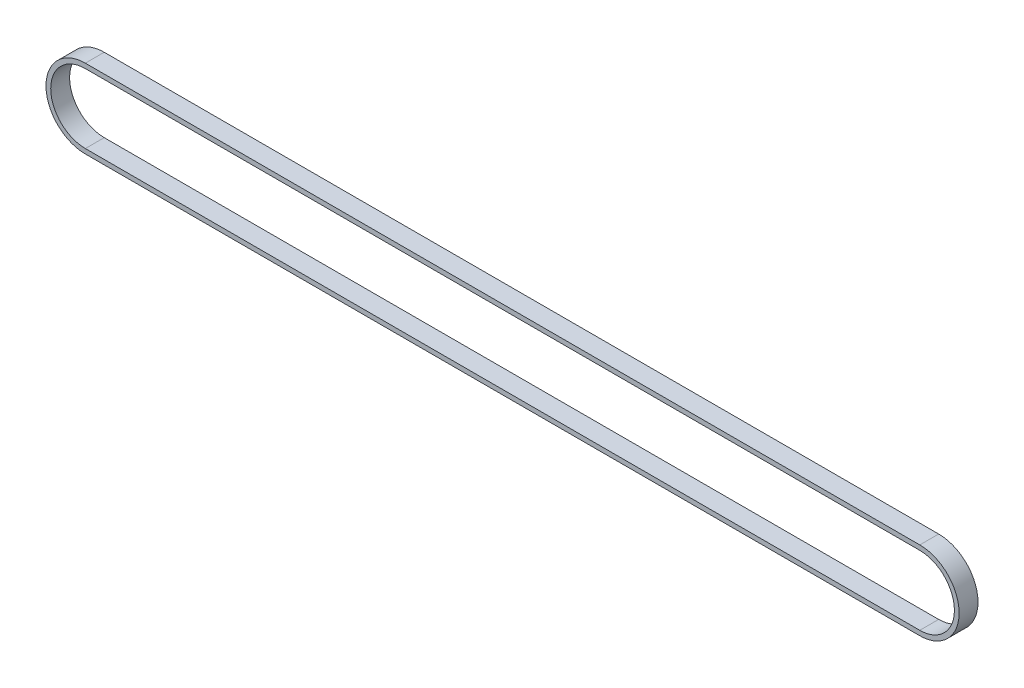
SolidWorks part; units mm, degrees
ref_plane "Alzado" through (0, 0, 0) normal (0, 0, 1) x (1, 0, 0)
ref_plane "Planta" through (0, 0, 0) normal (0, 1, 0) x (1, 0, 0)
ref_plane "Vista lateral" through (0, 0, 0) normal (1, 0, 0) x (0, 0, -1)
sketch "Croquis1" plane through (0, 0, 0) normal (0, 0, 1) x (1, 0, 0)
  line L0 (-11, 0) -> (-11, 13.8326) construction
  line L1 (276.17, 0) -> (276.17, 13.8326) construction
  line L2 (0, -11) -> (265.17, -11)
  line L3 (265.17, 11) -> (0, 11)
  line L4 (265.17, 12.5) -> (0, 12.5)
  line L5 (0, -12.5) -> (265.17, -12.5)
  arc A0 (0, 11) -> (0, -11) centre (0, 0) ccw
  arc A1 (265.17, -11) -> (265.17, 11) centre (265.17, 0) ccw
  arc A2 (0, 12.5) -> (0, -12.5) centre (0, 0) ccw
  arc A3 (265.17, -12.5) -> (265.17, 12.5) centre (265.17, 0) ccw
  dimension "D1" = 22
  dimension "D2" = 22
  dimension "D3" = 287.17
  dimension "D4" = 1.5
extrude "Saliente-Extruir1" add sketch "Croquis1" along normal blind 6
